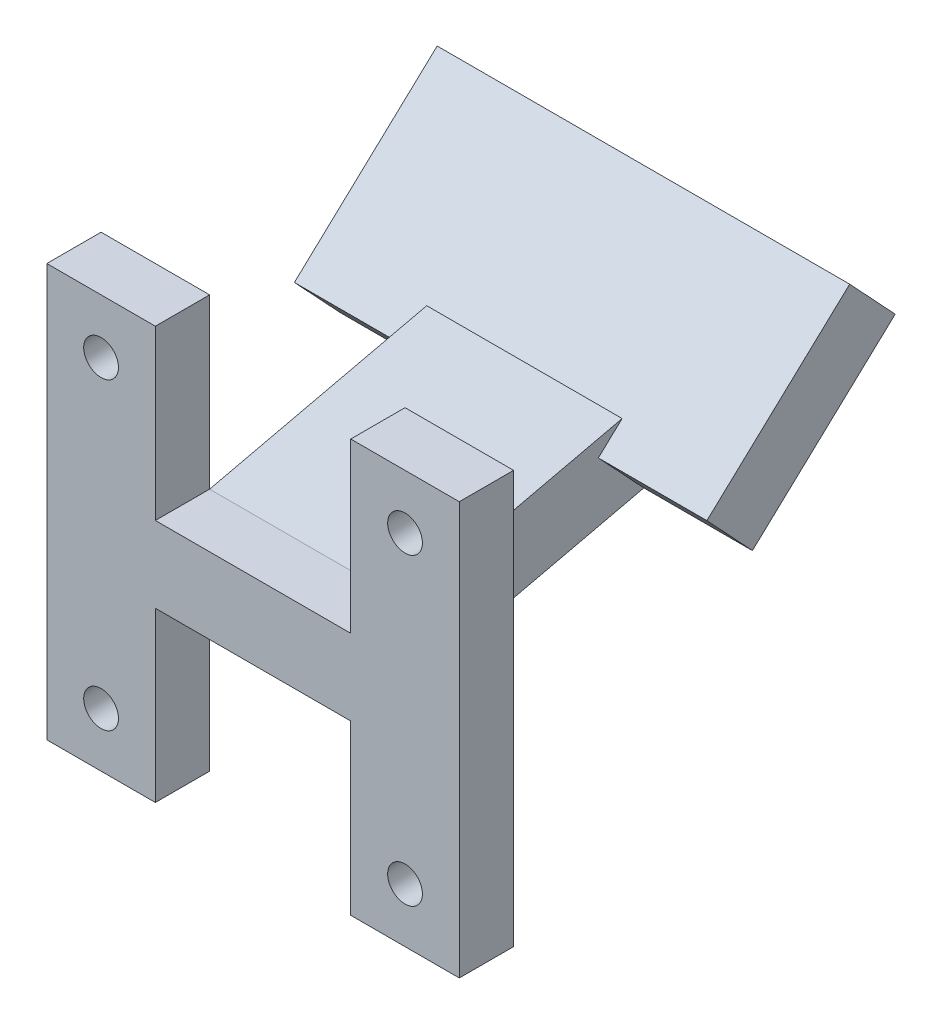
SolidWorks part; units mm, degrees
ref_plane "前视基准面" through (0, 0, 0) normal (0, 0, 1) x (1, 0, 0)
ref_plane "上视基准面" through (0, 0, 0) normal (0, 1, 0) x (1, 0, 0)
ref_plane "右视基准面" through (0, 0, 0) normal (1, 0, 0) x (0, 0, -1)
other "Configuration Table"
sketch "草图1" plane through (0, 0, 0) normal (0, 0, 1) x (1, 0, 0)
  line L0 (0, 0) -> (0, 38)
  line L1 (0, 38) -> (10, 38)
  line L2 (10, 38) -> (10, 22.5)
  line L3 (10, 22.5) -> (28, 22.5)
  line L4 (28, 22.5) -> (28, 38)
  line L5 (28, 38) -> (38, 38)
  line L6 (38, 38) -> (38, 0)
  line L7 (38, 0) -> (28, 0)
  line L8 (28, 0) -> (28, 15.5)
  line L9 (28, 15.5) -> (10, 15.5)
  line L10 (10, 15.5) -> (10, 0)
  line L11 (10, 0) -> (0, 0)
  line L12 (10, 38) -> (28, 38) construction
  line L13 (28, 0) -> (10, 0) construction
  line L15 (5, 33) -> (33, 33) construction
  line L16 (5, 33) -> (5, 5) construction
  line L17 (5, 5) -> (33, 5) construction
  line L18 (33, 33) -> (33, 5) construction
  circle A1 centre (5, 33) radius 1.6
  circle A2 centre (33, 33) radius 1.6
  circle A3 centre (33, 5) radius 1.6
  circle A4 centre (5, 5) radius 1.6
  dimension "D9" = 3.2
  dimension "D1" = 38
  dimension "D2" = 38
  dimension "D3" = 7
  dimension "D4" = 28
  dimension "D5" = 28
  dimension "D6" = 5
  dimension "D7" = 5
  dimension "D8" = 10
extrude "凸台-拉伸1" add sketch "草图1" along normal blind 5
sketch "草图2" plane through (38, 0, 0) normal (1, 0, 0) x (0, 0, -1)
  line L0 (-5, 22.5) -> (0, 22.5) construction
  line L1 (-5, 15.5) -> (0, 15.5) construction
  line L2 (-5, 22.5) -> (0, 22.5) construction
  line L3 (-5, 15.5) -> (0, 15.5) construction
  line L4 (0, 0) -> (0, 38) construction
  line L5 (0, 0) -> (0, 38) construction
  line L6 (0, 22.5) -> (20, 27.1336)
  line L7 (20, 27.1336) -> (30.9624, 37.372)
  line L8 (30.9624, 37.372) -> (35.1549, 32.883)
  line L9 (35.1549, 32.883) -> (22, 20.5969)
  line L10 (22, 20.5969) -> (0, 15.5)
  line L11 (0, 22.5) -> (0, 15.5)
  dimension "D1" = 150
  dimension "D2" = 20
  dimension "D3" = 22
  dimension "D4" = 18
  dimension "D5" = 15
extrude "凸台-拉伸2" add sketch "草图2" against normal up to surface (18 mm away) from surface at -10 up to face at (10, 30.25, 2.5) starting at face at (28, 30.25, 2.5)
sketch "草图4" plane through (0, 0.0267, 0.0249) normal (0, -0.7308, -0.6826) x (1, 0, 0)
  line L0 (10, -30.1369) -> (0, -30.1369)
  line L1 (0, -30.1369) -> (0, -48.1369)
  line L2 (0, -48.1369) -> (10, -48.1369)
  line L3 (10, -48.1369) -> (28, -48.1369)
  line L4 (28, -30.1369) -> (10, -30.1369)
  line L5 (10, -30.1369) -> (10, -48.1369)
  line L6 (10, -48.1369) -> (28, -48.1369)
  line L7 (28, -48.1369) -> (28, -30.1369)
  line L8 (28, -30.1369) -> (10, -30.1369) construction
  line L9 (10, -30.1369) -> (10, -48.1369) construction
  line L10 (10, -48.1369) -> (28, -48.1369) construction
  line L11 (28, -48.1369) -> (28, -30.1369) construction
  line L12 (28, -48.1369) -> (38, -48.1369)
  line L13 (38, -48.1369) -> (38, -30.1369)
  line L14 (38, -30.1369) -> (28, -30.1369)
  line L15 (10, -30.1369) -> (10, -48.1369)
  line L16 (28, -48.1369) -> (28, -30.1369)
  line M10 (10, -30.1369) -> (10, -48.1369)
  line M12 (28, -48.1369) -> (28, -30.1369)
  dimension "D1" = 0
extrude "凸台-拉伸3" add sketch "草图4" against normal up to surface (6.1423 mm away) contours L1 L2 L0 M10 | L13 L14 L12 M12 up to face at (19, 32.2528, -25.4812)
sketch "草图5" plane through (0, 0.0267, 0.0249) normal (0, -0.7308, -0.6826) x (1, 0, 0)
  line L0 (5, -43.1369) -> (33, -43.1369) construction
  line L1 (38, -48.1369) -> (38, -30.1369) construction
  line L2 (0, -48.1369) -> (38, -48.1369) construction
  circle A0 centre (5, -43.1369) radius 2
  circle A1 centre (33, -43.1369) radius 2
  dimension "D4" = 4
  dimension "D1" = 28
  dimension "D2" = 5
  dimension "D3" = 5
extrude "切除-拉伸1" cut sketch "草图5" against normal blind 5
